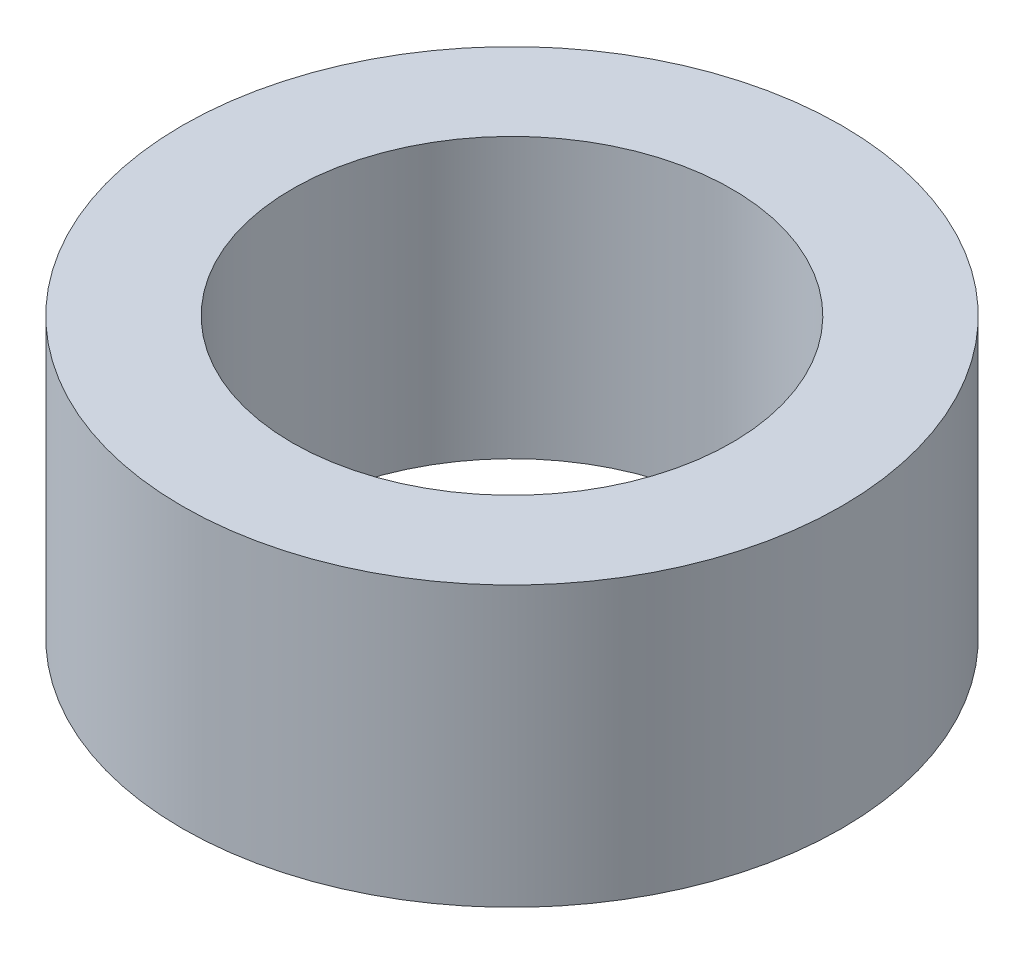
SolidWorks part; units mm, degrees
material "6061 Alloy"
ref_plane "Front Plane" through (0, 0, 0) normal (0, 0, 1) x (1, 0, 0)
ref_plane "Top Plane" through (0, 0, 0) normal (0, 1, 0) x (1, 0, 0)
ref_plane "Right Plane" through (0, 0, 0) normal (1, 0, 0) x (0, 0, -1)
sketch "Sketch1" plane through (0, 0, 0) normal (0, 1, 0) x (1, 0, 0)
  circle A1 centre (0, 0) radius 10
  circle A2 centre (0, 0) radius 15
  dimension "D1" = 20
  dimension "D2" = 5
extrude "Boss-Extrude1" add sketch "Sketch1" along normal blind 12.7
